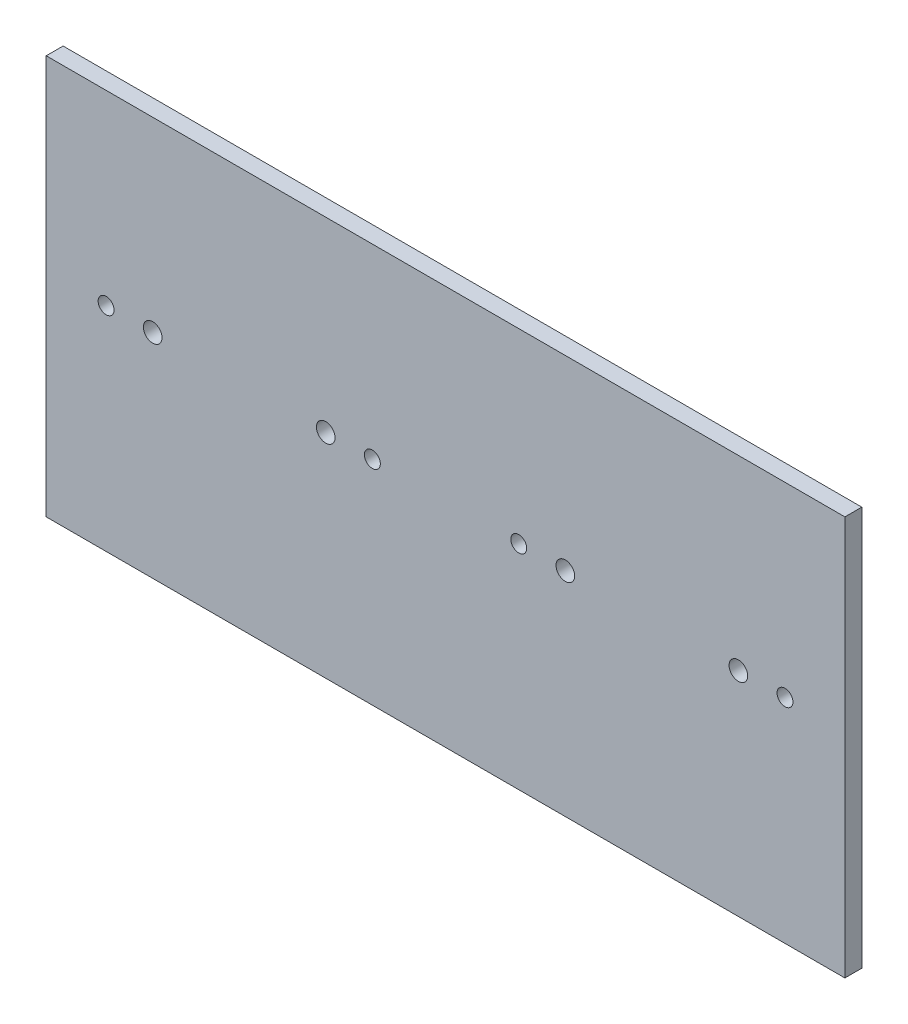
SolidWorks part; units mm, degrees
ref_plane "Front Plane" through (0, 0, 0) normal (0, 0, 1) x (1, 0, 0)
ref_plane "Top Plane" through (0, 0, 0) normal (0, 1, 0) x (1, 0, 0)
ref_plane "Right Plane" through (0, 0, 0) normal (1, 0, 0) x (0, 0, -1)
sketch "Sketch1" plane through (0, 0, 0) normal (0, 0, 1) x (1, 0, 0)
  line L0 (150, 150) -> (150, 0) construction
  line L1 (0, 0) -> (300, 0)
  line L2 (0, 0) -> (0, 150)
  line L3 (0, 150) -> (300, 150)
  line L4 (300, 0) -> (300, 150)
  circle A0 centre (22.5, 80) radius 2.995
  circle A1 centre (122.5, 80) radius 2.995
  circle A2 centre (277.5, 80) radius 2.995
  circle A3 centre (177.5, 80) radius 2.995
  circle A4 centre (40, 80) radius 3.5
  circle A5 centre (105, 80) radius 3.5
  circle A6 centre (195, 80) radius 3.5
  circle A7 centre (260, 80) radius 3.5
  dimension "D5" = 55
  dimension "D8" = 5.99
  dimension "D9" = 5.99
  dimension "D10" = 5.99
  dimension "D11" = 5.99
  dimension "D13" = 7
  dimension "D14" = 7
  dimension "D17" = 7
  dimension "D18" = 7
  dimension "D1" = 300
  dimension "D2" = 150
  dimension "D3" = 100
  dimension "D4" = 27.5
  dimension "D6" = 100
  dimension "D7" = 70
  dimension "D12" = 17.5
  dimension "D15" = 17.5
  dimension "D16" = 17.5
  dimension "D19" = 17.5
extrude "Boss-Extrude1" add sketch "Sketch1" along normal blind 6.35
